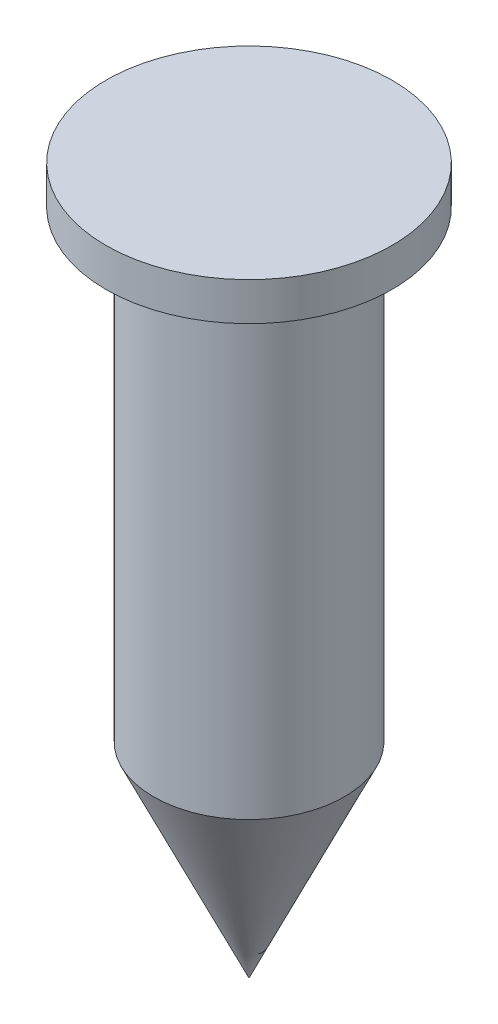
SolidWorks part; units mm, degrees
material "Plain Carbon Steel"
ref_plane "Front Plane" through (0, 0, 0) normal (0, 0, 1) x (1, 0, 0)
ref_plane "Top Plane" through (0, 0, 0) normal (0, 1, 0) x (1, 0, 0)
ref_plane "Right Plane" through (0, 0, 0) normal (1, 0, 0) x (0, 0, -1)
sketch "Sketch1" plane through (0, 0, 0) normal (0, 0, 1) x (1, 0, 0)
  line L0 (0, 0) -> (7.5, 0)
  line L1 (7.5, 0) -> (7.5, -2)
  line L2 (7.5, -2) -> (5, -2)
  line L3 (5, -2) -> (5, -26.2775)
  line L4 (5, -26.2775) -> (0, -37)
  line L5 (0, -37) -> (0, 0)
  line L6 (0, -42) -> (0, 5) construction
  dimension "D1" = 65
  dimension "D2" = 5
  dimension "D3" = 5
  dimension "D4" = 2
  dimension "D5" = 35
  dimension "D6" = 10
  dimension "D7" = 15
revolve "Revolve1" add sketch "Sketch1" angle 360 about L6
